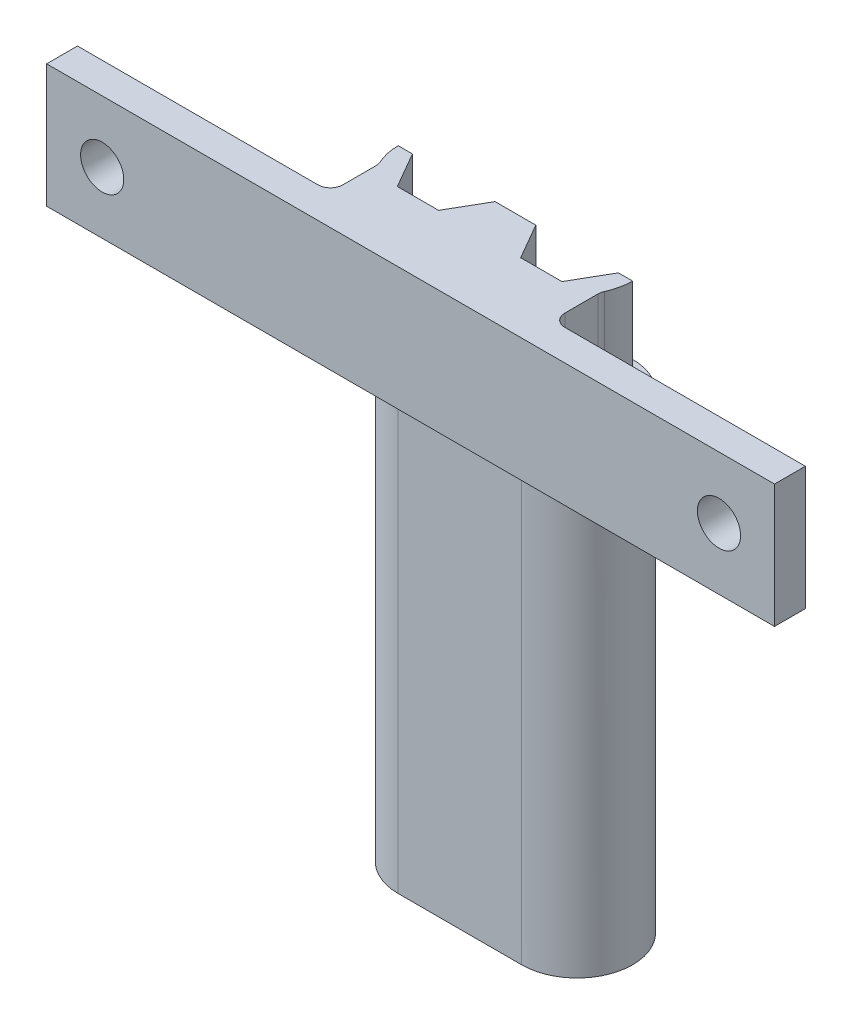
SolidWorks part; units mm, degrees
ref_plane "Front Plane" through (0, 0, 0) normal (0, 0, 1) x (1, 0, 0)
ref_plane "Top Plane" through (0, 0, 0) normal (0, 1, 0) x (1, 0, 0)
ref_plane "Right Plane" through (0, 0, 0) normal (1, 0, 0) x (0, 0, -1)
sketch "Sketch1" plane through (0, 0, 0) normal (0, 1, 0) x (1, 0, 0)
  line L0 (-5, 4.5) -> (5, 4.5)
  line L1 (5, -4.5) -> (-5, -4.5)
  circle A0 centre (-5, 0) radius 1.75
  circle A1 centre (5, 0) radius 1.75
  arc A2 (-5, 4.5) -> (-5, -4.5) centre (-5, 0) ccw
  arc A3 (5, -4.5) -> (5, 4.5) centre (5, 0) ccw
  dimension "D1" = 10
  dimension "D2" = 5
  dimension "D3" = 3.5
  dimension "D4" = 9
extrude "Boss-Extrude1" add sketch "Sketch1" along normal blind 48
sketch "Sketch2" plane through (0, 48, 0) normal (0, 1, 0) x (1, 0, 0)
  line L0 (-5, 0) -> (5, 0) construction
  line L1 (-1.6514, 0) -> (-3.3257, 2.9)
  line L2 (-3.3257, 2.9) -> (-6.6743, 2.9)
  line L3 (-6.6743, 2.9) -> (-8.3486, 0)
  line L4 (-8.3486, 0) -> (-6.6743, -2.9)
  line L5 (-6.6743, -2.9) -> (-3.3257, -2.9)
  line L6 (-3.3257, -2.9) -> (-1.6514, 0)
  line L7 (0, 2.0527) -> (0, -1.1173) construction
  line L8 (3.3257, -2.9) -> (1.6514, 0)
  line L9 (6.6743, -2.9) -> (3.3257, -2.9)
  line L10 (8.3486, 0) -> (6.6743, -2.9)
  line L11 (6.6743, 2.9) -> (8.3486, 0)
  line L12 (3.3257, 2.9) -> (6.6743, 2.9)
  line L13 (1.6514, 0) -> (3.3257, 2.9)
  circle A0 centre (-5, 0) radius 2.9 construction
  circle A1 centre (5, 0) radius 2.9 construction
  dimension "D1" = 5.8
extrude "Cut-Extrude1" cut sketch "Sketch2" against normal blind 44
sketch "Sketch4" plane through (0, 48, 0) normal (0, 1, 0) x (1, 0, 0)
  line L0 (-5, -4.5) -> (5, -4.5) construction
  line L1 (-5, -4.5) -> (5, -4.5)
  line L3 (-10.5, -8.5) -> (10.5, -8.5)
  line L7 (-10.5, -8.5) -> (-29.5, -8.5)
  line L8 (10.5, -8.5) -> (29.5, -8.5)
  line L9 (-29.5, -8.5) -> (-29.5, -6)
  line L10 (-29.5, -6) -> (-9, -6)
  line L11 (29.5, -8.5) -> (29.5, -6)
  line L12 (29.5, -6) -> (9, -6)
  line L13 (9, -6) -> (9, -2.0616)
  line L14 (-9, -6) -> (-9, -2.0616)
  arc A1 (5, -4.5) -> (5, 4.5) centre (5, 0) ccw construction
  arc A2 (-5, 4.5) -> (-5, -4.5) centre (-5, 0) ccw construction
  arc A4 (-9, -2.0616) -> (-5, -4.5) centre (-5, 0) ccw
  arc A5 (5, -4.5) -> (9, -2.0616) centre (5, 0) ccw
  point P17 (10.5, -4.5)
  dimension "D4" = 19
  dimension "D5" = 5.5
  dimension "D2" = 21
  dimension "D1" = 4
  dimension "D3" = 19
extrude "Boss-Extrude2" add sketch "Sketch4" against normal blind 10
sketch "Sketch5" plane through (0, 48, 0) normal (0, 1, 0) x (1, 0, 0)
  line L0 (-9.5, 0) -> (9.5, 0)
  line L1 (-5, 4.5) -> (5, 4.5)
  arc A0 (-5, 4.5) -> (-9.5, 0) centre (-5, 0) ccw
  arc A1 (9.5, 0) -> (5, 4.5) centre (5, 0) ccw
extrude "Cut-Extrude2" cut sketch "Sketch5" against normal blind 10
sketch "Sketch6" plane through (0, 0, 8.5) normal (0, 0, 1) x (1, 0, 0)
  line L0 (-29.5, 43) -> (29.5, 43) construction
  line L1 (-29.5, 38) -> (-29.5, 48) construction
  line L2 (29.5, 38) -> (29.5, 48) construction
  line L3 (-25, 43) -> (25, 43) construction
  circle A0 centre (-25, 43) radius 1.75
  circle A1 centre (25, 43) radius 1.75
  circle A2 centre (-25, 43) radius 2.85 construction
  circle A3 centre (25, 43) radius 2.85 construction
  point P9 (0, 43)
  point P14 (0, 43)
  dimension "D2" = 3.5
  dimension "D3" = 3.5
  dimension "D4" = 5.7
  dimension "D5" = 5.7
  dimension "D1" = 50
fillet "Fillet3" radius 1 4 edges at (9, 43, 2.0616) (9, 43, 6) (-9, 43, 6) (-9, 43, 2.0616)
extrude "Cut-Extrude3" cut sketch "Sketch6" against normal blind 10
